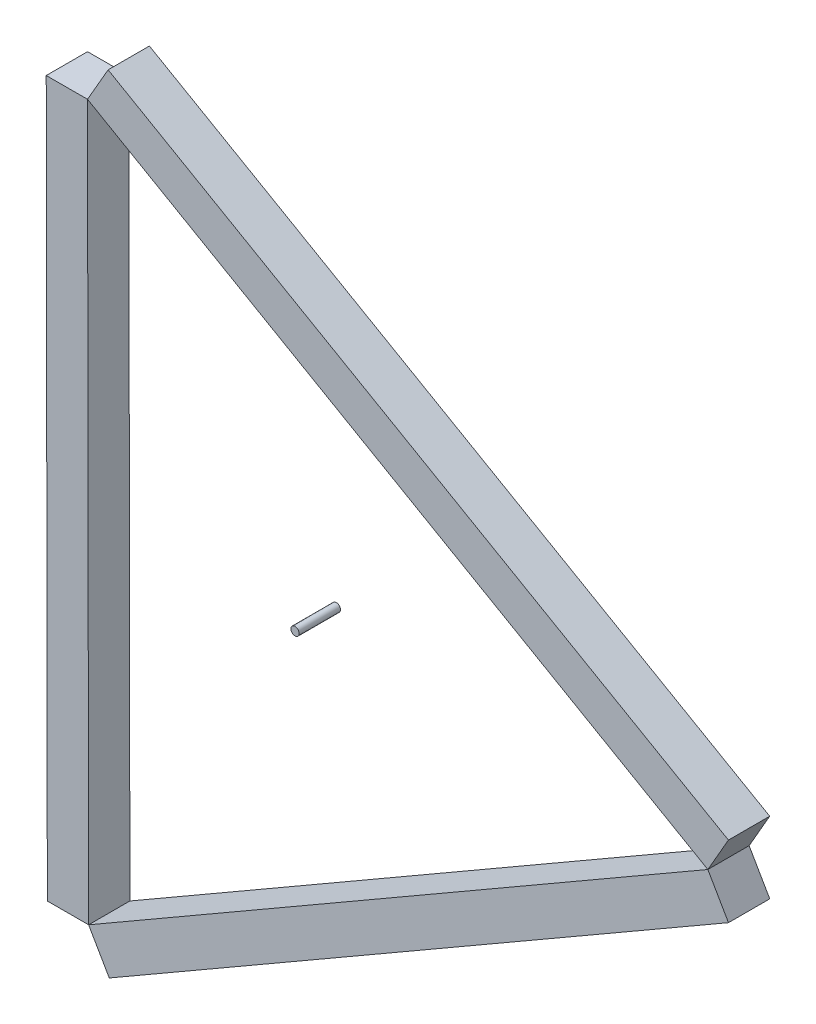
SolidWorks part; units mm, degrees
ref_plane "Front Plane" through (0, 0, 0) normal (0, 0, 1) x (1, 0, 0)
ref_plane "Top Plane" through (0, 0, 0) normal (0, 1, 0) x (1, 0, 0)
ref_plane "Right Plane" through (0, 0, 0) normal (1, 0, 0) x (0, 0, -1)
sketch "Sketch1" plane through (0, 0, 0) normal (0, 0, 1) x (1, 0, 0)
  line L0 (1528.9664, 0) -> (0, 0) construction
  line L1 (0, 0) -> (-918.1607, 1590.301) construction
  line L2 (0, 0) -> (-694.8278, -1203.4771) construction
  line L3 (0, 0) -> (-1542.2771, 0) construction
  line L4 (0, 0) -> (625.4451, 1083.3028) construction
  line L5 (0, 0) -> (646.494, -1119.7604) construction
  line L6 (-1000, 0) -> (-502.6514, 864.4892)
  line L7 (-502.6514, 864.4892) -> (502.6514, 864.4892)
  line L8 (502.6514, 864.4892) -> (1000, 0)
  line L9 (1000, 0) -> (500, -866.0254)
  line L10 (500, -866.0254) -> (-500, -866.0254)
  line L11 (-500, -866.0254) -> (-1000, 0)
  line L12 (1224.9953, 228.0643) -> (1224.9953, -221.9357)
  line L13 (-810.0072, 946.8449) -> (-420.2957, 1171.8449)
  line L14 (-810.0072, 946.8449) -> (-585.0072, 557.1335)
  line L15 (-585.0072, 557.1335) -> (-195.2957, 782.1335)
  line L16 (-420.2957, 1171.8449) -> (-195.2957, 782.1335)
  line L17 (-810.0072, 946.8449) -> (-195.2957, 782.1335) construction
  line L18 (-585.0072, 557.1335) -> (-420.2957, 1171.8449) construction
  line L19 (-500, -866.0254) -> (-502.6514, 864.4892)
  line L20 (-502.6514, 864.4892) -> (1000, 0)
  line L21 (1000, 0) -> (-500, -866.0254)
  line L22 (-599.9999, -866.1786) -> (-602.6513, 864.336)
  line L23 (-946.6097, 983.4474) -> (-58.6932, 745.5309) construction
  line L24 (-452.7842, 951.1682) -> (1049.8673, 86.679)
  line L25 (1050, -86.6025) -> (-450, -952.6279)
  line L26 (-602.6513, 864.336) -> (-502.6514, 864.4892)
  line L27 (1224.9953, -221.9357) -> (774.9953, -221.9357)
  line L28 (774.9953, 228.0643) -> (774.9953, -221.9357)
  line L29 (-452.7842, 951.1682) -> (-502.6514, 864.4892)
  line L30 (1224.9953, 228.0643) -> (774.9953, 228.0643)
  line L31 (1049.8673, 86.679) -> (1000, 0)
  line L32 (-414.9882, -1174.9092) -> (-804.6996, -949.9092)
  line L33 (1000, 0) -> (1050, -86.6025)
  line L34 (-450, -952.6279) -> (-500, -866.0254)
  line L35 (-804.6996, -949.9092) -> (-579.6996, -560.1978)
  line L36 (-189.9882, -785.1978) -> (-579.6996, -560.1978)
  line L37 (-599.9999, -866.1786) -> (-500, -866.0254)
  line L38 (-414.9882, -1174.9092) -> (-189.9882, -785.1978)
  circle A0 centre (0, 0) radius 750 construction
  circle A1 centre (0, 0) radius 1000 construction
  circle A2 centre (0, 0) radius 10
  point P31 (0, 0)
  point P32 (-18.2945, 0.0494)
  point P45 (0, 0)
  dimension "D1" = 1500
  dimension "D2" = 2000
  dimension "D10" = 20
  dimension "D3" = 120
  dimension "D4" = 1005.3029
  dimension "D5" = 60
  dimension "D6" = 60
  dimension "D7" = 60
  dimension "D8" = 450
  dimension "D9" = 100
  dimension "D11" = 60
  dimension "D13" = 3
extrude "Boss-Extrude1" add sketch "Sketch1" along normal mid plane 100 contours L36 L19 L15 L14 L22 L35 | L22 L14 L15 L19 L6 | L26 L22 L6 | L30 L24 L16 L15 L20 L28 | L24 L7 L20 L15 L16 | L24 L29 L7 | L21 L28 L27 L25 L9 | L33 L9 L25 | L24 L30 L28 L20 L8 | L31 L24 L8 | L38 L25 L27 L28 L21 L36 | L25 L38 L36 L21 L10 | L34 L25 L10 | L19 L36 L35 L22 L11 | L22 L37 L11 | A2
